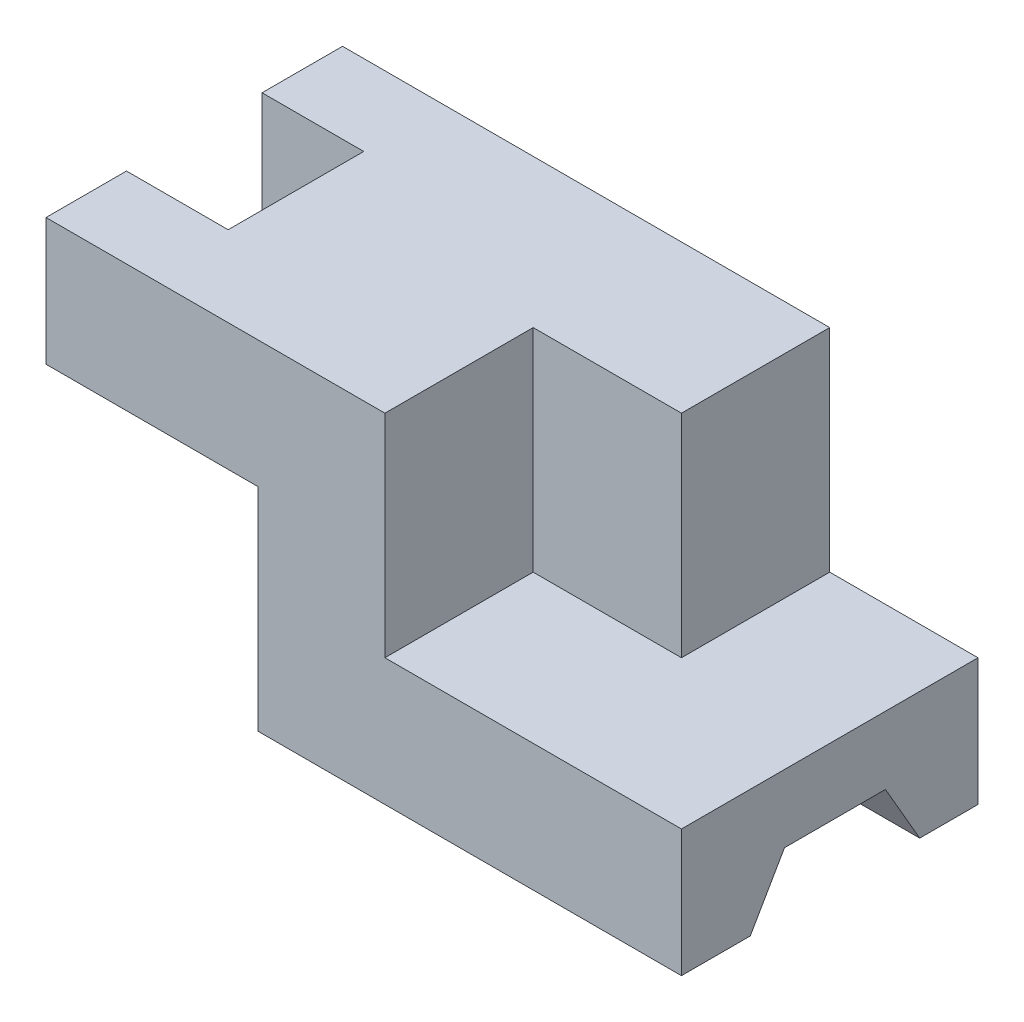
SolidWorks part; units mm, degrees
ref_plane "정면" through (0, 0, 0) normal (0, 0, 1) x (1, 0, 0)
ref_plane "윗면" through (0, 0, 0) normal (0, 1, 0) x (1, 0, 0)
ref_plane "우측면" through (0, 0, 0) normal (1, 0, 0) x (0, 0, -1)
sketch "Sketch2" plane through (0, 0, 0) normal (0, 0, 1) x (1, 0, 0)
  line L1 (0, 0) -> (75, 0)
  line L2 (0, 0) -> (0, 40)
  line L3 (0, 40) -> (75, 40)
  line L4 (75, 0) -> (75, 40)
  line L5 (0, 0) -> (25, 0)
  line L6 (0, 0) -> (0, 25)
  line L7 (0, 25) -> (25, 25)
  line L8 (25, 0) -> (25, 25)
  line L9 (40, 40) -> (75, 40)
  line L10 (40, 40) -> (40, 15)
  line L11 (40, 15) -> (75, 15)
  line L12 (75, 40) -> (75, 15)
  dimension "D1" = 25
  dimension "D2" = 50
  dimension "D3" = 75
  dimension "D4" = 15
  dimension "D5" = 40
  dimension "D6" = 40
extrude "Boss-Extrude1" add sketch "Sketch2" along normal blind 35 contours L11 L10 L3 L2 L7 L8 L1 L4
sketch "Sketch3" plane through (0, 40, 0) normal (0, 1, 0) x (1, 0, 0)
  line L0 (0, -35) -> (0, 0) construction
  line L1 (0, -9.5) -> (12, -9.5)
  line L2 (0, -9.5) -> (0, -25.5)
  line L3 (0, -25.5) -> (12, -25.5)
  line L4 (12, -9.5) -> (12, -25.5)
  line L5 (0, -35) -> (40, -35) construction
  point P13 (0, 0)
  point P14 (0, 0)
  point P15 (0, 0)
  dimension "D1" = 9.5
  dimension "D2" = 16
  dimension "D3" = 12
extrude "Cut-Extrude1" cut sketch "Sketch3" against normal blind 35 contours L3 L4 L1 L2
sketch "Sketch4" plane through (0, 40, 0) normal (0, 1, 0) x (1, 0, 0)
  line L1 (40, 0) -> (57.5, 0)
  line L2 (40, 0) -> (40, -17.5)
  line L3 (40, -17.5) -> (57.5, -17.5)
  line L4 (57.5, 0) -> (57.5, -17.5)
  dimension "D1" = 17.5
  dimension "D2" = 17.5
extrude "Boss-Extrude2" add sketch "Sketch4" against normal up to next
sketch "Sketch5" plane through (75, 0, 0) normal (1, 0, 0) x (0, 0, -1)
  line L0 (-26.8789, 0) -> (-22.8375, 7)
  line L1 (-35, 0) -> (0, 0) construction
  line L2 (-22.8375, 7) -> (-10.9204, 7)
  line L3 (-10.9204, 7) -> (-6.8789, 0)
  line L4 (-6.8789, 0) -> (-26.8789, 0)
  dimension "D1" = 20
  dimension "D2" = 60
  dimension "D3" = 60
  dimension "D4" = 7
extrude "Cut-Extrude2" cut sketch "Sketch5" against normal through all contours L0 L2 L3 L4
